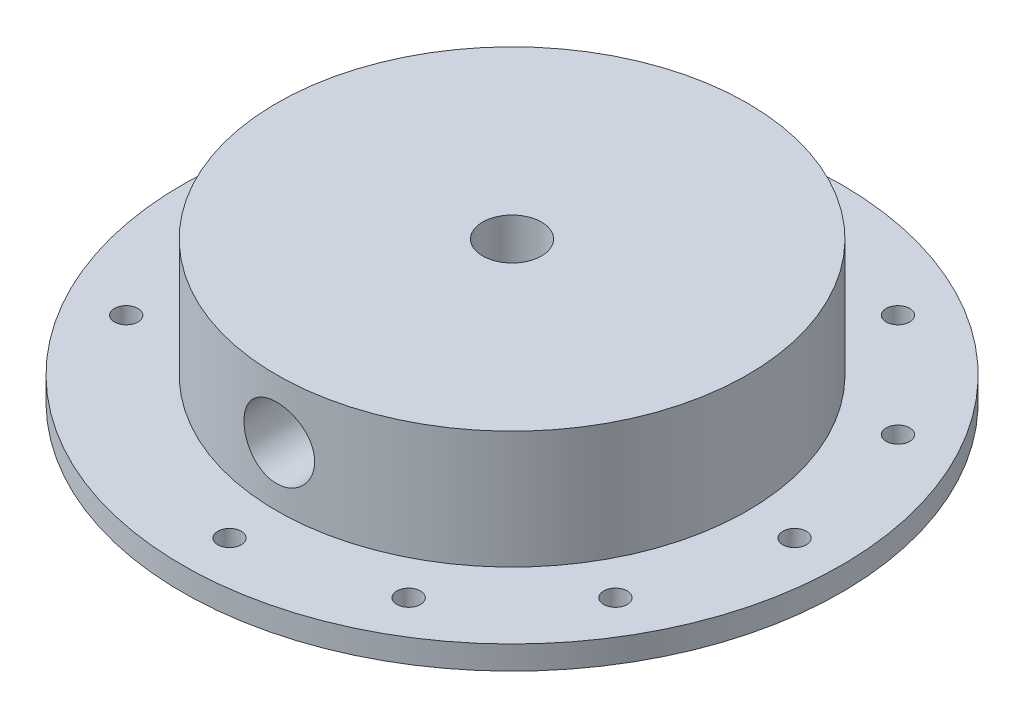
SolidWorks part; units mm, degrees
material "AISI 316 Annealed Stainless Steel Bar (SS)"
ref_plane "Front Plane" through (0, 0, 0) normal (0, 0, 1) x (1, 0, 0)
ref_plane "Top Plane" through (0, 0, 0) normal (0, 1, 0) x (1, 0, 0)
ref_plane "Right Plane" through (0, 0, 0) normal (1, 0, 0) x (0, 0, -1)
sketch "Sketch1" plane through (0, 0, 0) normal (0, 0, 1) x (1, 0, 0)
  line L0 (7.9375, 38.1) -> (7.9375, 11.1125)
  line L1 (38.1, 0) -> (88.9, 0)
  line L2 (88.9, 0) -> (88.9, 6.35)
  line L3 (88.9, 6.35) -> (63.5, 6.35)
  line L4 (63.5, 6.35) -> (63.5, 38.1)
  line L5 (63.5, 38.1) -> (7.9375, 38.1)
  line L6 (0, 0) -> (0, 33.4189) construction
  arc A0 (7.9375, 11.1125) -> (38.1, 0) centre (38.1, 46.4911) ccw
  dimension "D1" = 15.875
  dimension "D2" = 177.8
  dimension "D3" = 25.4
  dimension "D4" = 6.35
  dimension "D5" = 38.1
  dimension "D6" = 76.2
  dimension "D7" = 11.1125
revolve "Revolve1" add sketch "Sketch1" angle 360 about L6
sketch "Sketch3" plane through (0, 6.35, 0) normal (0, 1, 0) x (1, 0, 0)
  line L0 (0, 0) -> (0, -101.6) construction
  point P4 (0, -101.6)
  dimension "D1" = 101.6
hole_wizard "1/4 (0.25) Diameter Hole1" positions "Sketch4" profile "Sketch5" hole size "1/4" standard "ANSI Inch" end condition through all
sketch "Sketch4" plane through (0, 6.35, 0) normal (0, 1, 0) x (1, 0, 0)
  line L2 (0, 0) -> (0, -76.2) construction
  point P0 (0, -76.2)
  dimension "D1" = 76.2
sketch "Sketch5" plane through (0, 6.35, 76.2) normal (1, 0, 0) x (0, 0, 1)
  line L0 (0, 0) -> (0, 6.35)
  line L1 (0, 6.35) -> (3.175, 6.35)
  line L2 (3.175, 6.35) -> (3.175, 0)
  line L5 (3.175, 0) -> (0, 0)
  line L11 (0, -6.35) -> (0, 107.95) construction
  dimension "Thru Hole Dia." = 6.35
  dimension "Thru Hole Depth" = 6.35
pattern_circular "CirPattern2" count 12 over 360 about axis through (0, 0, 0) along (0, 1, 0) skipping 11 of "1/4 (0.25) Diameter Hole1"
sketch "Sketch6" plane through (0, 0, 0) normal (0, 0, 1) x (1, 0, 0)
  line L0 (0, 38.1) -> (0, 6.35) construction
  line L1 (7.9375, 38.1) -> (-7.9375, 38.1) construction
  line L2 (88.9, 6.35) -> (-88.9, 6.35) construction
  circle A0 centre (0, 22.225) radius 9.525
  dimension "D1" = 19.05
extrude "Cut-Extrude1" cut sketch "Sketch6" along normal through all
